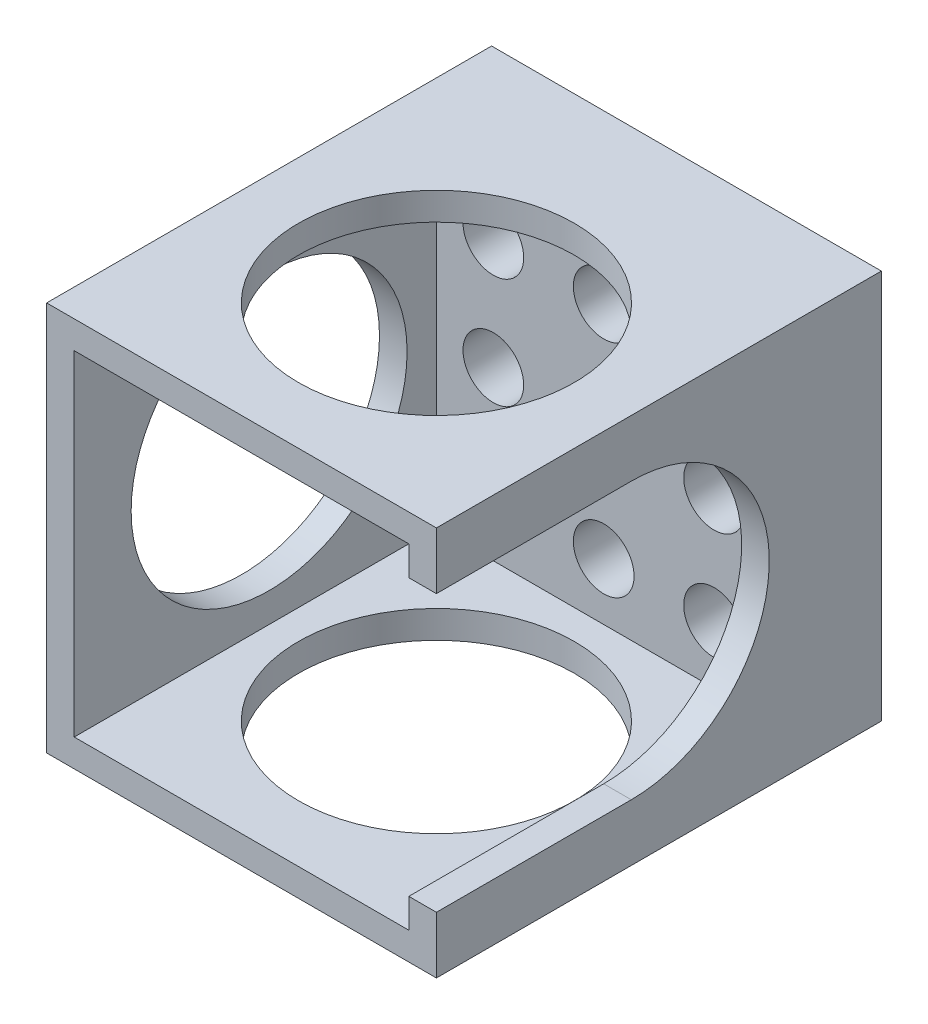
SolidWorks part; units mm, degrees
ref_plane "Front Plane" through (0, 0, 0) normal (0, 0, 1) x (1, 0, 0)
ref_plane "Top Plane" through (0, 0, 0) normal (0, 1, 0) x (1, 0, 0)
ref_plane "Right Plane" through (0, 0, 0) normal (1, 0, 0) x (0, 0, -1)
sketch "Sketch1" plane through (0, 0, 0) normal (0, 1, 0) x (1, 0, 0)
  line L1 (-19.25, -19.25) -> (19.25, -19.25)
  line L2 (-19.25, -19.25) -> (-19.25, 19.25)
  line L3 (-19.25, 19.25) -> (19.25, 19.25)
  line L4 (19.25, -19.25) -> (19.25, 19.25)
  line L5 (-19.25, -19.25) -> (19.25, 19.25) construction
  line L6 (-19.25, 19.25) -> (19.25, -19.25) construction
  line L7 (-22.425, -22.425) -> (22.425, -22.425)
  line L8 (-22.425, -22.425) -> (-22.425, 22.425)
  line L9 (-22.425, 22.425) -> (22.425, 22.425)
  line L10 (22.425, -22.425) -> (22.425, 22.425)
  line L11 (-22.425, -22.425) -> (22.425, 22.425) construction
  line L12 (-22.425, 22.425) -> (22.425, -22.425) construction
  point P0 (0, 0)
  point P6 (0, 0)
  dimension "D1" = 38.5
  dimension "D2" = 38.5
  dimension "D3" = 3.175
  dimension "D4" = 3.175
extrude "Boss-Extrude1" add sketch "Sketch1" along normal mid plane 38.5
sketch "Sketch2" plane through (0, 19.25, 0) normal (0, 1, 0) x (1, 0, 0)
  line L1 (-22.425, 22.425) -> (22.425, 22.425)
  line L2 (-22.425, 22.425) -> (-22.425, -22.425)
  line L3 (-22.425, -22.425) -> (22.425, -22.425)
  line L4 (22.425, 22.425) -> (22.425, -22.425)
extrude "Boss-Extrude2" add sketch "Sketch2" along normal blind 3.175
sketch "Sketch3" plane through (0, -19.25, 0) normal (0, -1, 0) x (1, 0, 0)
  line L1 (22.425, -22.425) -> (-22.425, -22.425)
  line L2 (22.425, -22.425) -> (22.425, 22.425)
  line L3 (22.425, 22.425) -> (-22.425, 22.425)
  line L4 (-22.425, -22.425) -> (-22.425, 22.425)
extrude "Boss-Extrude3" add sketch "Sketch3" along normal blind 3.175
sketch "Sketch5" plane through (0, -22.425, -22.425) normal (0, 1, 0) x (1, 0, 0)
  circle A0 centre (0, -22.425) radius 15.875
  dimension "D1" = 31.75
extrude "Cut-Extrude1" cut sketch "Sketch5" along normal through all from surface at 0 starting at face at (0, -22.425, 0)
sketch "Sketch8" plane through (0, 0, -22.425) normal (0, 0, -1) x (-1, 0, 0)
  line L0 (-12.7, 12.7) -> (0, 12.7) construction
  line L1 (-22.425, -22.425) -> (22.425, -22.425)
  line L2 (-22.425, 22.425) -> (-22.425, -22.425)
  line L3 (-22.425, 22.425) -> (22.425, 22.425)
  line L4 (22.425, -22.425) -> (22.425, 22.425)
  circle A0 centre (-12.7, 12.7) radius 2.2225
  circle A1 centre (0, 12.7) radius 2.2225
  circle A2 centre (12.7, 12.7) radius 2.2225
  circle A3 centre (0, 0) radius 2.2225
  circle A4 centre (12.7, 0) radius 2.2225
  circle A5 centre (0, -12.7) radius 2.2225
  circle A6 centre (12.7, -12.7) radius 2.2225
  circle A7 centre (-12.7, 0) radius 2.2225
  circle A8 centre (-12.7, -12.7) radius 2.2225
  dimension "D1" = 4.445
  dimension "D2" = 12.7
  dimension "D3" = 12.7
  dimension "D6" = 12.7
  dimension "D4" = 3
  dimension "D5" = 3
extrude "Boss-Extrude4" add sketch "Sketch8" along normal blind 6.35
sketch "Sketch9" plane through (0, 0, -19.25) normal (0, 0, 1) x (1, 0, 0)
  line L0 (12.7, 12.7) -> (0, 12.7) construction
  circle A0 centre (12.7, 12.7) radius 3.4925
  circle A1 centre (0, 12.7) radius 3.4925
  circle A2 centre (-12.7, 12.7) radius 3.4925
  circle A3 centre (0, 0) radius 3.4925
  circle A4 centre (-12.7, 0) radius 3.4925
  circle A5 centre (0, -12.7) radius 3.4925
  circle A6 centre (-12.7, -12.7) radius 3.4925
  circle A7 centre (12.7, 0) radius 3.4925
  circle A8 centre (12.7, -12.7) radius 3.4925
  dimension "D1" = 6.985
  dimension "D4" = 12.7
  dimension "D2" = 3
  dimension "D3" = 3
extrude "Cut-Extrude4" cut sketch "Sketch9" against normal blind 6.35
sketch "Sketch10" plane through (0, 0, 22.425) normal (0, 0, 1) x (1, 0, 0)
  line L0 (-22.425, 22.425) -> (-22.425, -22.425) construction
  line L1 (-19.25, -19.25) -> (19.25, -19.25)
  line L2 (-19.25, -19.25) -> (-19.25, 19.25)
  line L3 (-19.25, 19.25) -> (19.25, 19.25)
  line L4 (19.25, -19.25) -> (19.25, 19.25)
  line L5 (-19.25, -19.25) -> (19.25, 19.25) construction
  line L6 (-19.25, 19.25) -> (19.25, -19.25) construction
  line L7 (-22.425, 22.425) -> (22.425, 22.425) construction
  point P0 (0, 0)
  dimension "D1" = 3.175
  dimension "D2" = 3.175
extrude "Cut-Extrude5" cut sketch "Sketch10" against normal up to next
sketch "Sketch7" plane through (0, 0, 0) normal (-1, 0, 0) x (0, 0, 1)
  line L0 (0, 15.875) -> (25, 15.875)
  line L2 (25, 15.875) -> (25, -15.875)
  line L3 (25, -15.875) -> (0, -15.875)
  arc A0 (0, 15.875) -> (0, -15.875) centre (0, 0) ccw
  point P7 (25, -12.7)
  dimension "D1" = 31.75
extrude "Cut-Extrude3" cut sketch "Sketch7" against normal through all from surface at 0 starting at plane "Right Plane"
sketch "Sketch11" plane through (0, 0, 0) normal (1, 0, 0) x (0, 0, -1)
  circle A0 centre (0, 0) radius 15.875
  dimension "D1" = 31.75
extrude "Cut-Extrude6" cut sketch "Sketch11" against normal through all
